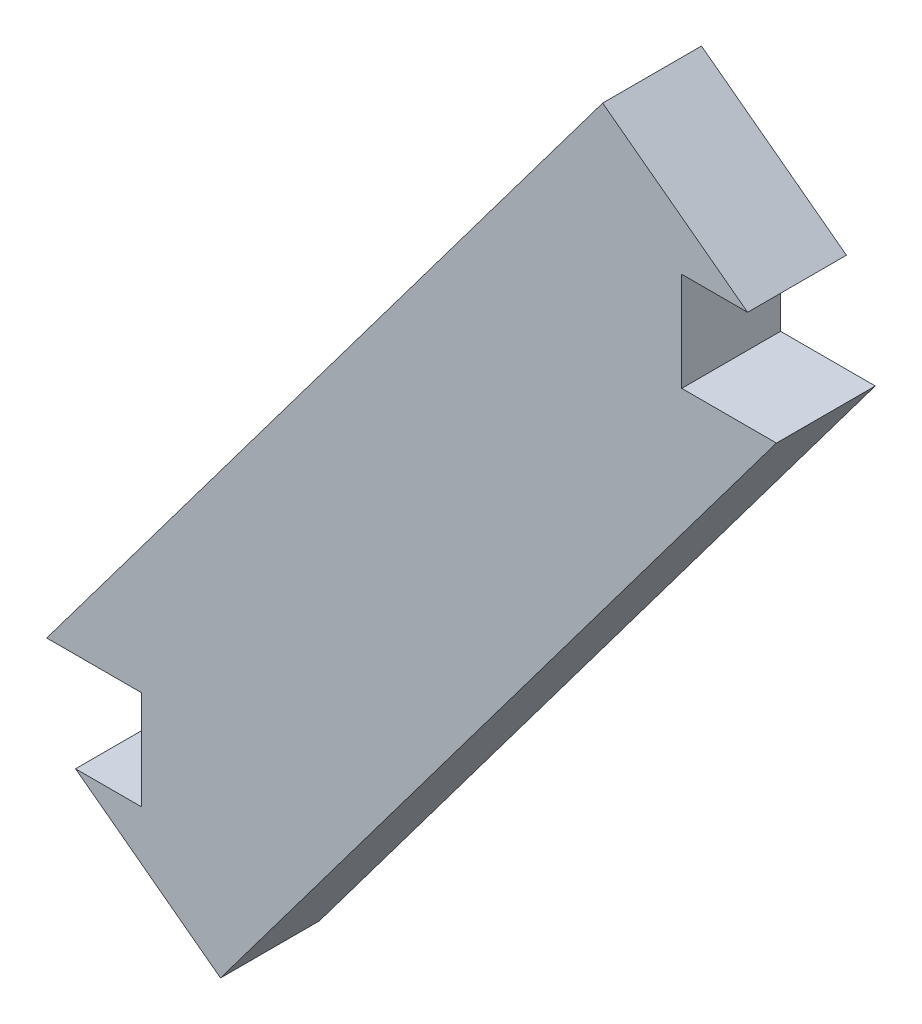
SolidWorks part; units mm, degrees
ref_plane "Front Plane" through (0, 0, 0) normal (0, 0, 1) x (1, 0, 0)
ref_plane "Top Plane" through (0, 0, 0) normal (0, 1, 0) x (1, 0, 0)
ref_plane "Right Plane" through (0, 0, 0) normal (1, 0, 0) x (0, 0, -1)
sketch "Sketch1" plane through (0, 0, 0) normal (0, 0, 1) x (1, 0, 0)
  line L0 (0, 0) -> (28.575, 38.1)
  line L1 (0, 0) -> (10.16, -7.62)
  line L2 (28.575, 38.1) -> (38.735, 30.48)
  line L3 (10.16, -7.62) -> (38.735, 30.48)
  line L4 (3.175, -2.3812) -> (6.35, -2.3812)
  line L5 (6.35, -2.3812) -> (6.35, 2.3813)
  line L6 (6.35, 2.3813) -> (1.7859, 2.3813)
  line L7 (36.9491, 28.0988) -> (32.385, 28.0988)
  line L8 (32.385, 28.0988) -> (32.385, 32.8612)
  line L10 (32.385, 32.8612) -> (35.56, 32.8612)
  point P11 (23.1503, 28.7796)
  dimension "D1" = 38.1
  dimension "D2" = 12.7
  dimension "D3" = 6.35
  dimension "D4" = 4.7625
  dimension "D5" = 4.7625
  dimension "D6" = 2.3813
  dimension "D7" = 7.62
  dimension "D8" = 2.3813
  dimension "D9" = 6.35
extrude "Boss-Extrude1" add sketch "Sketch1" along normal blind 4.7625 contours L8 L10 L2 L0 L6 L5 L4 L1 L3 L7
